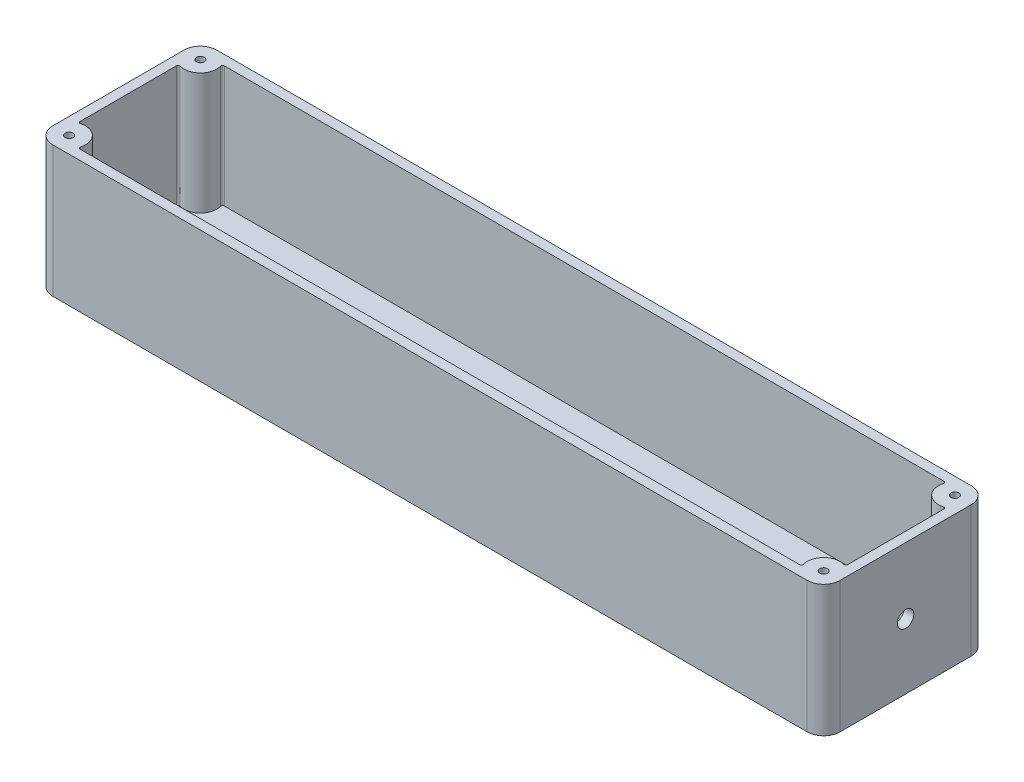
SolidWorks part; units mm, degrees
ref_plane "Front Plane" through (0, 0, 0) normal (0, 0, 1) x (1, 0, 0)
ref_plane "Top Plane" through (0, 0, 0) normal (0, 1, 0) x (1, 0, 0)
ref_plane "Right Plane" through (0, 0, 0) normal (1, 0, 0) x (0, 0, -1)
sketch "Sketch1" plane through (0, 0, 0) normal (0, 1, 0) x (1, 0, 0)
  line L5 (-115, 25) -> (115, 25)
  line L6 (-120, 20) -> (-120, -20)
  line L7 (-115, -25) -> (115, -25)
  line L8 (120, 20) -> (120, -20)
  line L9 (-120, 25) -> (120, -25) construction
  line L10 (-120, -25) -> (120, 25) construction
  arc A0 (115, 25) -> (120, 20) centre (115, 20) cw
  arc A1 (115, -25) -> (120, -20) centre (115, -20) ccw
  arc A2 (-120, -20) -> (-115, -25) centre (-115, -20) ccw
  arc A3 (-115, 25) -> (-120, 20) centre (-115, 20) ccw
  point P0 (0, 0)
  dimension "D3" = 5
  dimension "D1" = 240
  dimension "D2" = 50
extrude "Boss-Extrude1" add sketch "Sketch1" along normal blind 40
sketch "Sketch2" plane through (0, 40, 0) normal (0, 1, 0) x (1, 0, 0)
  line L0 (109.7085, 22) -> (-109.7085, 22)
  line L1 (-117, 14.7085) -> (-117, -14.7085)
  line L2 (-109.7085, -22) -> (109.7085, -22)
  line L3 (117, -14.7085) -> (117, 14.7085)
  line L4 (115, 25) -> (-115, 25)
  line L5 (-120, 20) -> (-120, -20)
  line L6 (-115, -25) -> (115, -25)
  line L7 (120, -20) -> (120, 20)
  line L8 (115, 25) -> (-115, 25)
  line L9 (-120, 20) -> (-120, -20)
  line L10 (-115, -25) -> (115, -25)
  line L11 (120, -20) -> (120, 20)
  line L12 (-117, 20) -> (-117, -20) construction
  line L13 (115, 22) -> (-115, 22) construction
  line L14 (-115, -22) -> (115, -22) construction
  line L15 (117, -20) -> (117, 20) construction
  line L16 (0, 0) -> (0, -10.1974) construction
  line L17 (0, 0) -> (4.4004, 0) construction
  arc A0 (-115, 25) -> (-120, 20) centre (-115, 20) ccw
  arc A1 (-120, -20) -> (-115, -25) centre (-115, -20) ccw
  arc A2 (120, 20) -> (115, 25) centre (115, 20) ccw
  arc A3 (115, -25) -> (120, -20) centre (115, -20) ccw
  arc A4 (120, 20) -> (115, 25) centre (115, 20) ccw
  arc A5 (-115, 25) -> (-120, 20) centre (-115, 20) ccw
  arc A6 (-120, -20) -> (-115, -25) centre (-115, -20) ccw
  arc A7 (115, -25) -> (120, -20) centre (115, -20) ccw
  arc A8 (120, 20) -> (115, 25) centre (115, 20) ccw
  arc A9 (-115, 25) -> (-120, 20) centre (-115, 20) ccw
  arc A10 (-120, -20) -> (-115, -25) centre (-115, -20) ccw
  arc A11 (115, -25) -> (120, -20) centre (115, -20) ccw
  arc A16 (-115, 22) -> (-117, 20) centre (-115, 20) ccw construction
  arc A17 (-117, -20) -> (-115, -22) centre (-115, -20) ccw construction
  arc A18 (115, -22) -> (117, -20) centre (115, -20) ccw construction
  arc A19 (117, 20) -> (115, 22) centre (115, 20) ccw construction
  arc A20 (-109.7085, 22) -> (-110.1895, 21.3636) centre (-109.7085, 21.5) ccw
  arc A21 (-116.3636, 15.1895) -> (-117, 14.7085) centre (-116.5, 14.7085) ccw
  arc A22 (116.3636, 15.1895) -> (117, 14.7085) centre (116.5, 14.7085) cw
  arc A23 (109.7085, 22) -> (110.1895, 21.3636) centre (109.7085, 21.5) cw
  arc A24 (116.3636, -15.1895) -> (117, -14.7085) centre (116.5, -14.7085) ccw
  arc A25 (109.7085, -22) -> (110.1895, -21.3636) centre (109.7085, -21.5) ccw
  arc A26 (-109.7085, -22) -> (-110.1895, -21.3636) centre (-109.7085, -21.5) cw
  arc A27 (-116.3636, -15.1895) -> (-117, -14.7085) centre (-116.5, -14.7085) cw
  arc A28 (-116.3636, 15.1895) -> (-110.1895, 21.3636) centre (-115, 20) ccw
  arc A29 (-110.1895, -21.3636) -> (-116.3636, -15.1895) centre (-115, -20) ccw
  arc A30 (116.3636, -15.1895) -> (110.1895, -21.3636) centre (115, -20) ccw
  arc A31 (110.1895, 21.3636) -> (116.3636, 15.1895) centre (115, 20) ccw
  dimension "D3" = 1
  dimension "D4" = 1
  dimension "D1" = 0
  dimension "D2" = 3
extrude "Cut-Extrude1" cut sketch "Sketch2" against normal blind 37 contours A31 A23 L0 A20 A28 A21 L1 A27 A29 A26 L2 A25 A30 A24 L3 A22
sketch "Sketch5" plane through (0, 40, 0) normal (0, 1, 0) x (1, 0, 0)
  line L0 (0, 0) -> (8.56, 0) construction
  line L1 (0, 11.6184) -> (0, 0) construction
  line L4 (115, 25) -> (-115, 25)
  line L6 (115, 25) -> (-115, 25)
  line L12 (-120, 20) -> (-120, -20)
  line L13 (-120, 20) -> (-120, -20)
  line L14 (-115, -25) -> (115, -25)
  line L15 (-115, -25) -> (115, -25)
  line L16 (120, -20) -> (120, 20)
  line L17 (120, -20) -> (120, 20)
  circle A0 centre (-115, 20) radius 3 construction
  circle A1 centre (115, 20) radius 3 construction
  circle A2 centre (115, -20) radius 3 construction
  circle A3 centre (-115, -20) radius 3 construction
  arc A16 (120, 20) -> (115, 25) centre (115, 20) ccw
  arc A17 (120, 20) -> (115, 25) centre (115, 20) ccw
  arc A18 (-115, 25) -> (-120, 20) centre (-115, 20) ccw
  arc A19 (-115, 25) -> (-120, 20) centre (-115, 20) ccw
  arc A20 (-120, -20) -> (-115, -25) centre (-115, -20) ccw
  arc A21 (-120, -20) -> (-115, -25) centre (-115, -20) ccw
  arc A22 (115, -25) -> (120, -20) centre (115, -20) ccw
  arc A23 (115, -25) -> (120, -20) centre (115, -20) ccw
  dimension "D1" = 0
hole_wizard "M2 Clearance Hole1" positions "3DSketch2" profile "Sketch6" hole size "M2" standard "ISO"
sketch3d "3DSketch2"
  point P0 (-115, 40, -20)
  point P3 (-115, 40, 20)
  point P6 (115, 40, 20)
  point P9 (115, 40, -20)
sketch "Sketch6" plane through (-115, 40, -20) normal (1, 0, 0) x (0, 0, 1)
  line L0 (0, 0) -> (0, 15.721)
  line L1 (0, 15.721) -> (1.2, 15)
  line L2 (1.2, 15) -> (1.2, 0)
  line L5 (1.2, 0) -> (0, 0)
  line L10 (0, 15.721) -> (-1.2, 15) construction
  line L11 (0, -6.35) -> (0, 107.95) construction
  dimension "Hole Dia." = 2.4
  dimension "Hole Depth" = 15
  dimension "Drill Angle" = 118
sketch "Sketch7" plane through (120, 0, 0) normal (1, 0, 0) x (0, 0, -1)
  circle A0 centre (0, 19.8178) radius 2.5
  dimension "D1" = 5
extrude "Cut-Extrude2" cut sketch "Sketch7" against normal blind 7
